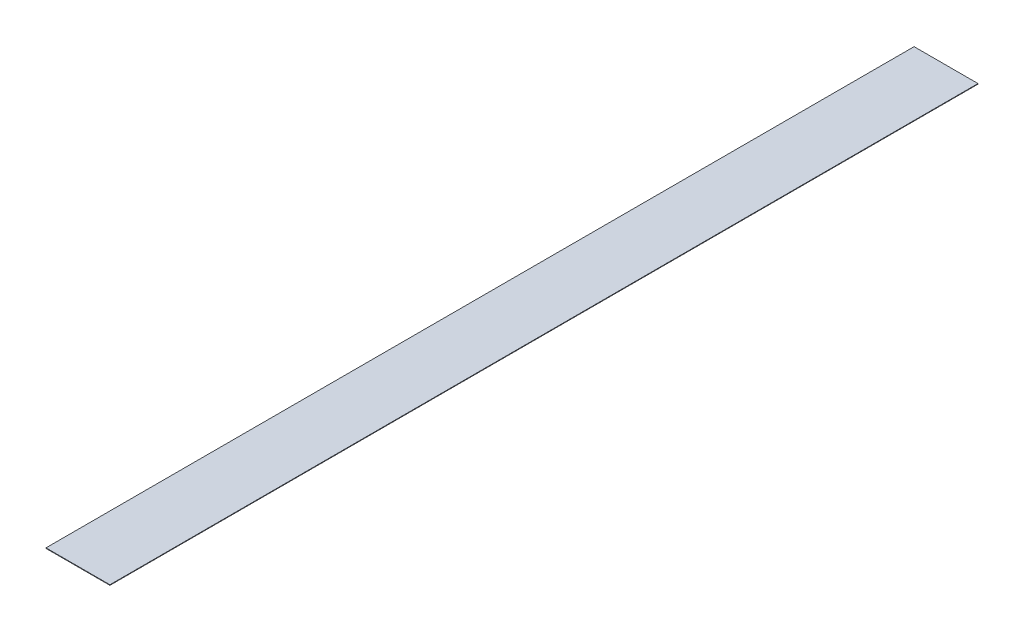
SolidWorks part; units mm, degrees
ref_plane "Front Plane" through (0, 0, 0) normal (0, 0, 1) x (1, 0, 0)
ref_plane "Top Plane" through (0, 0, 0) normal (0, 1, 0) x (1, 0, 0)
ref_plane "Right Plane" through (0, 0, 0) normal (1, 0, 0) x (0, 0, -1)
sketch "Esquisse1" plane through (0, 0, 0) normal (0, 1, 0) x (1, 0, 0)
  line L1 (-600, 8150) -> (600, 8150)
  line L2 (-600, 8150) -> (-600, -8150)
  line L3 (-600, -8150) -> (600, -8150)
  line L4 (600, 8150) -> (600, -8150)
  line L5 (-600, 8150) -> (600, -8150) construction
  line L6 (-600, -8150) -> (600, 8150) construction
  point P0 (0, 0)
extrude "Boss.-Extru.1" add sketch "Esquisse1" along normal blind 10
